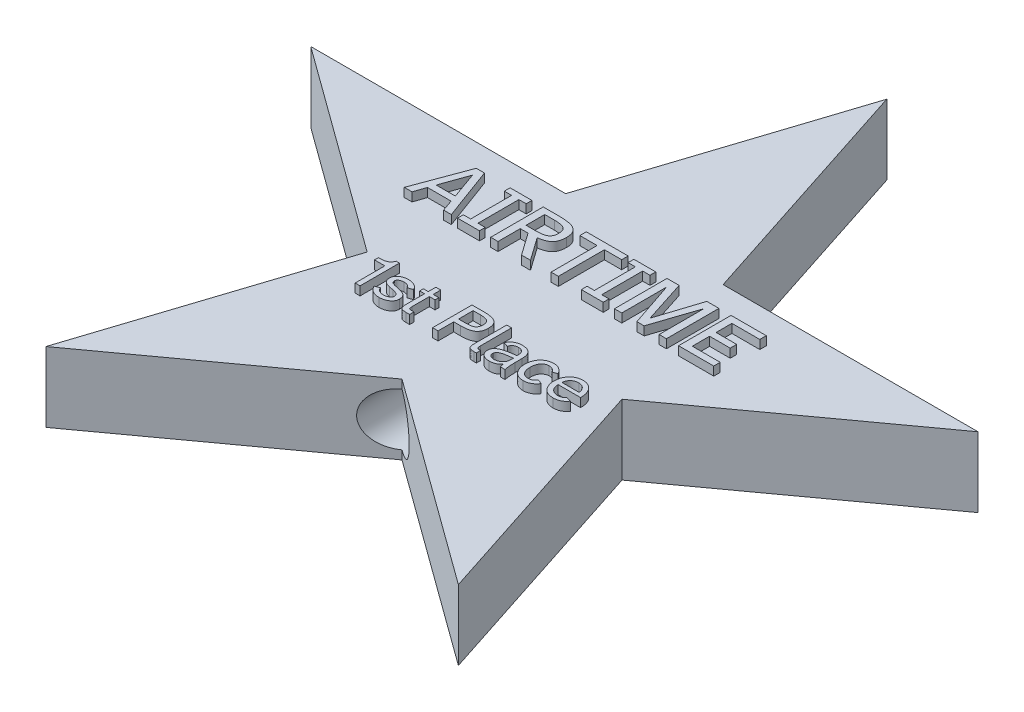
SolidWorks part; units mm, degrees
ref_plane "Front Plane" through (0, 0, 0) normal (0, 0, 1) x (1, 0, 0)
ref_plane "Top Plane" through (0, 0, 0) normal (0, 1, 0) x (1, 0, 0)
ref_plane "Right Plane" through (0, 0, 0) normal (1, 0, 0) x (0, 0, -1)
sketch "Sketch1" plane through (0, 0, 0) normal (0, 1, 0) x (1, 0, 0)
  line L0 (0, 0) -> (8.9942, -27.6813)
  line L1 (8.9942, -27.6813) -> (38.1, -27.6813)
  line L2 (38.1, -27.6813) -> (14.5529, -44.7892)
  line L3 (14.5529, -44.7892) -> (23.5471, -72.4705)
  line L4 (23.5471, -72.4705) -> (0, -55.3625)
  line L5 (0, -55.3625) -> (-23.5471, -72.4705)
  line L6 (-23.5471, -72.4705) -> (-14.5529, -44.7892)
  line L7 (-14.5529, -44.7892) -> (-38.1, -27.6813)
  line L8 (-38.1, -27.6813) -> (-8.9942, -27.6813)
  line L9 (-8.9942, -27.6813) -> (0, 0)
  point P3 (23.5471, -72.4705)
  dimension "D1" = 76.2
extrude "Boss-Extrude1" add sketch "Sketch1" along normal blind 8 contours L8 L9 L0 L1 L2 L3 L4 L5 L6 L7
sketch "Sketch2" plane through (0, 8, 0) normal (0, 1, 0) x (1, 0, 0)
  line L0 (0, 0) -> (0, -55.3625) construction
  text T0 "1st Place\r\n" font "Atkinson Hyperlegible" height 4.5
  text T1 "AIRTIME" font "Atkinson Hyperlegible" height 6
extrude "Boss-Extrude2" add sketch "Sketch2" along normal blind 1
ref_plane "Plane1" through (0, 0, 60) normal (0, 0, 1) x (1, 0, 0)
sketch "Sketch3" plane through (0, 0, 60) normal (0, 0, 1) x (1, 0, 0)
  line L0 (0, 8) -> (0, 0) construction
  circle A0 centre (0, 4) radius 3
  dimension "D1" = 6
extrude "Cut-Extrude1" cut sketch "Sketch3" against normal blind 9
